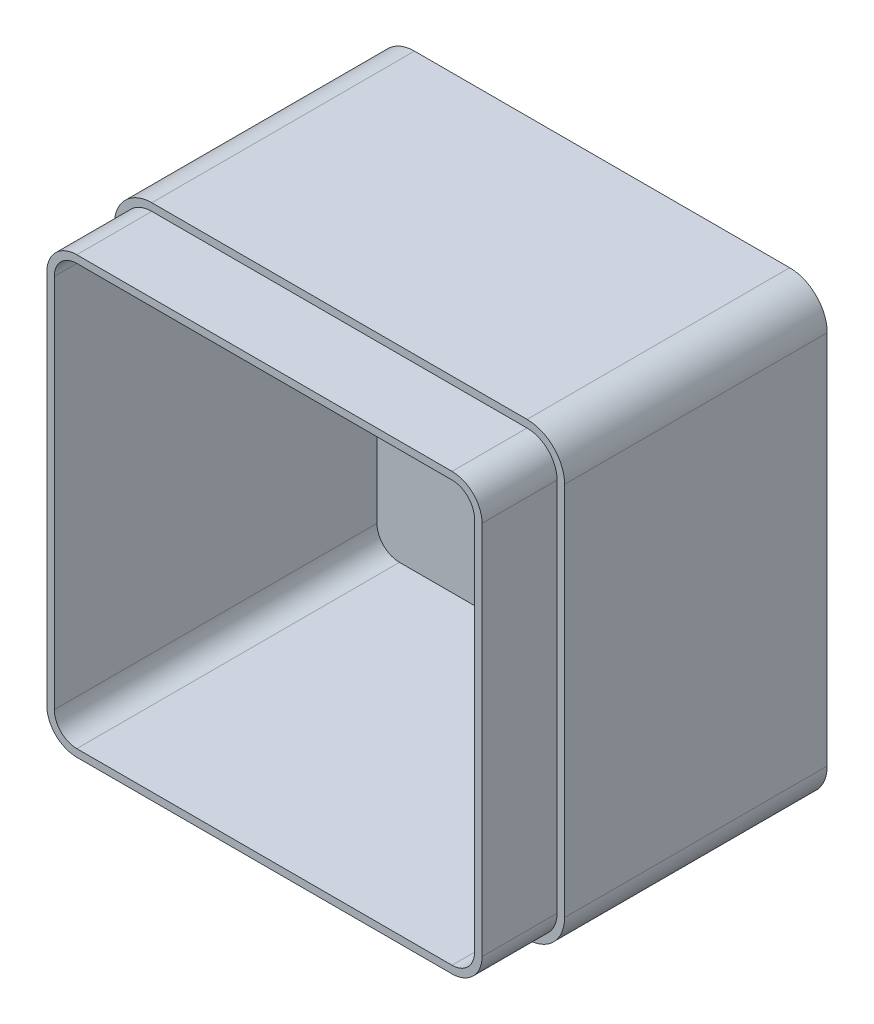
SolidWorks part; units mm, degrees
ref_plane "Front Plane" through (0, 0, 0) normal (0, 0, 1) x (1, 0, 0)
ref_plane "Top Plane" through (0, 0, 0) normal (0, 1, 0) x (1, 0, 0)
ref_plane "Right Plane" through (0, 0, 0) normal (1, 0, 0) x (0, 0, -1)
sketch "Sketch1" plane through (0, 0, 0) normal (0, 0, 1) x (1, 0, 0)
  line L1 (0, 0) -> (-120, 0)
  line L2 (0, 0) -> (0, 120)
  line L3 (0, 120) -> (-120, 120)
  line L4 (-120, 0) -> (-120, 120)
  dimension "D1" = 120
  dimension "D2" = 120
extrude "Boss-Extrude1" add sketch "Sketch1" along normal blind 90
fillet "Fillet1" radius 10 4 edges at (-120, 0, 45) (-120, 120, 45) (0, 0, 45) (0, 120, 45)
shell "Shell1" thickness 4
sketch "Sketch4" plane through (0, 0, 90) normal (0, 0, 1) x (1, 0, 0)
  line L0 (-118, 110) -> (-118, 10)
  line L1 (-110, 2) -> (-10, 2)
  line L2 (-2, 10) -> (-2, 110)
  line L3 (-10, 118) -> (-110, 118)
  line L4 (-120, 110) -> (-120, 10)
  line L5 (-110, 0) -> (-10, 0)
  line L6 (0, 10) -> (0, 110)
  line L7 (-10, 120) -> (-110, 120)
  line L8 (-120, 110) -> (-120, 10)
  line L9 (-110, 0) -> (-10, 0)
  line L10 (0, 10) -> (0, 110)
  line L11 (-10, 120) -> (-110, 120)
  arc A0 (-118, 10) -> (-110, 2) centre (-110, 10) ccw
  arc A1 (-10, 2) -> (-2, 10) centre (-10, 10) ccw
  arc A2 (-2, 110) -> (-10, 118) centre (-10, 110) ccw
  arc A3 (-110, 118) -> (-118, 110) centre (-110, 110) ccw
  arc A4 (-120, 10) -> (-110, 0) centre (-110, 10) ccw
  arc A5 (-10, 0) -> (0, 10) centre (-10, 10) ccw
  arc A6 (0, 110) -> (-10, 120) centre (-10, 110) ccw
  arc A7 (-110, 120) -> (-120, 110) centre (-110, 110) ccw
  arc A8 (-120, 10) -> (-110, 0) centre (-110, 10) ccw
  arc A9 (-10, 0) -> (0, 10) centre (-10, 10) ccw
  arc A10 (0, 110) -> (-10, 120) centre (-10, 110) ccw
  arc A11 (-110, 120) -> (-120, 110) centre (-110, 110) ccw
  dimension "D1" = 0
  dimension "D2" = 2
extrude "Cut-Extrude2" cut sketch "Sketch4" against normal blind 20
